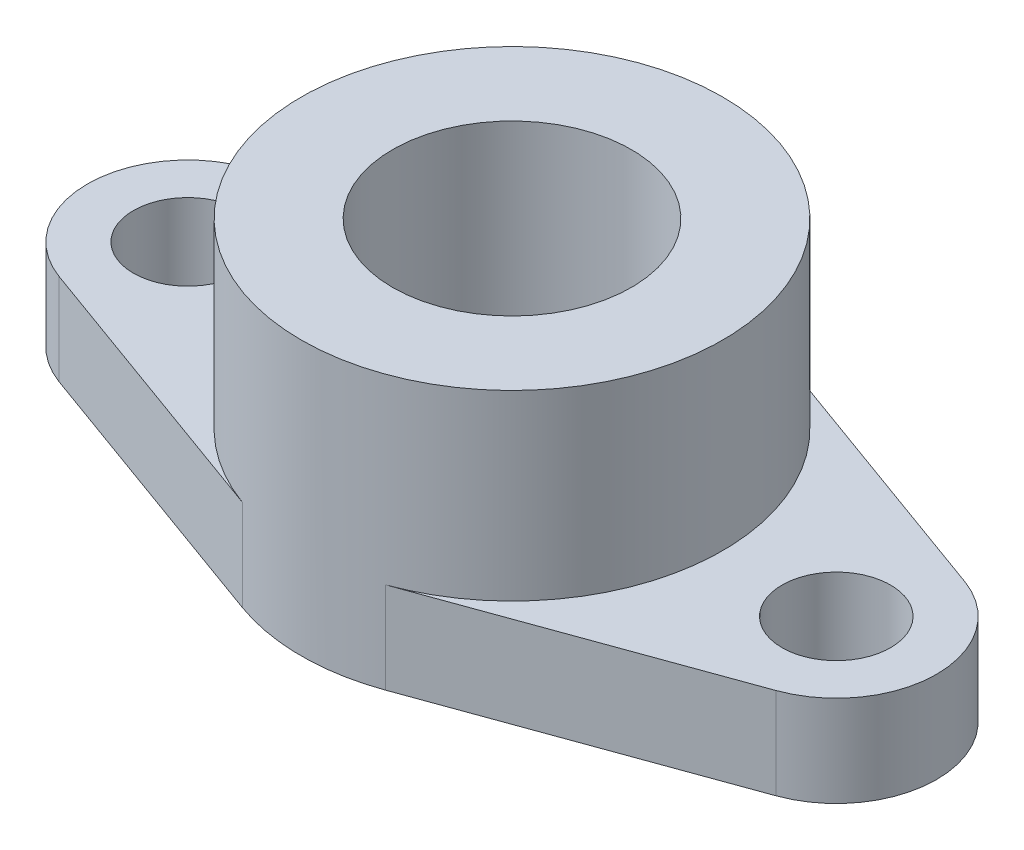
SolidWorks part; units mm, degrees
ref_plane "Front Plane" through (0, 0, 0) normal (0, 0, 1) x (1, 0, 0)
ref_plane "Top Plane" through (0, 0, 0) normal (0, 1, 0) x (1, 0, 0)
ref_plane "Right Plane" through (0, 0, 0) normal (1, 0, 0) x (0, 0, -1)
sketch "Sketch1" plane through (0, 0, 0) normal (0, 1, 0) x (1, 0, 0)
  line L0 (0, 0) -> (6.5484, 0) construction
  line L1 (0, 0) -> (17.78, 0) construction
  line L2 (19.651, 5.172) -> (3.9286, 10.8597)
  line L3 (3.9286, -10.8597) -> (19.651, -5.172)
  line L4 (0, 0) -> (-17.78, 0) construction
  line L5 (-19.651, 5.172) -> (-3.9286, 10.8597)
  line L6 (-19.651, -5.172) -> (-3.9286, -10.8597)
  circle A0 centre (0, 0) radius 4.826
  circle A1 centre (0, 0) radius 6.5484 construction
  arc A2 (3.9286, 10.8597) -> (3.9286, -10.8597) centre (0, 0) ccw construction
  circle A3 centre (17.78, 0) radius 2.9766
  arc A4 (19.651, -5.172) -> (19.651, 5.172) centre (17.78, 0) ccw
  circle A5 centre (0, 0) radius 11.5484 construction
  circle A6 centre (-17.78, 0) radius 2.9766
  arc A7 (-19.651, 5.172) -> (-19.651, -5.172) centre (-17.78, 0) ccw
  arc A10 (-3.9286, -10.8597) -> (3.9286, -10.8597) centre (0, 0) ccw
  arc A11 (3.9286, 10.8597) -> (-3.9286, 10.8597) centre (0, 0) ccw
  dimension "D1" = 9.652
  dimension "D2" = 13.0969
  dimension "D3" = 23.0969
  dimension "D5" = 5.9531
  dimension "D7" = 5.9531
  dimension "D6" = 5.5
  dimension "D4" = 17.78
  dimension "D8" = 17.78
extrude "Boss-Extrude1" add sketch "Sketch1" along normal blind 5
sketch "Sketch2" plane through (0, 5, 0) normal (0, 1, 0) x (1, 0, 0)
  circle A0 centre (0, 0) radius 11.5484
  arc A1 (-3.9286, -10.8597) -> (3.9286, -10.8597) centre (0, 0) ccw construction
  circle A2 centre (0, 0) radius 6.5484
  dimension "D1" = 13.0969
extrude "Boss-Extrude2" add sketch "Sketch2" along normal blind 10
equation "\"z\" = 8\t\t\t\t'number of blades"
equation "\"de\" = 0.43in\t\t\t'entrance eye diameter"
equation "\"de_length\" = 4mm\t\t'entrance eye consistent length"
equation "\"d_exit\" = 0.18in \t\t'throat aka d1"
equation "\"d2\" = 2.1in \t\t\t'outer diameter of the impeller"
equation "\"b2\" = .2in\t\t\t'tip height from disc surface at d2; slightly higher than d_exit"
equation "\"b1\" = \"b2\" + (\"d2\"/2 - \"de\"/2)*tan(\"theta\") \t\t\t'tip height from disc surface at inlet eye"
equation "\"theta\" = 12\t\t\t'angle of blades from inner to outer "
equation "\"ae\" = 3.14*(\"de\"^2)/4\t\t'entrance eye area'"
equation "\"ce\" = 3.14*\"de\"\t\t'entrance eye circumference"
equation "\"av_ratio\" = .325\t\t'ratio of av/ae at N_s of 470, range is .275 to .375, .325 ideal. High ratio means bigger area means smaller blades"
equation "\"av\" = \"ae\"*\"av_ratio\"\t\t'area between just two blades"
equation "\"s_open\" = \"av\"/\"b1\"\t\t'width of open area"
equation "\"s\"=\"ce\" - \"z\"*\"s_open\""
equation "\"min blade thickness\" = .15in"
equation "\"bearing OD\" = 30mm"
equation "\"bearing ID\"= 10mm"
equation "\"bearing depth\"= 9mm"
equation "\"bearing outer race thickness\"= 1mm"
equation "\"bearing inner race thickness\"= 1mm"
equation "\"bearing bore\" = \"bearing depth\" + 1mm"
equation "\"lower seal OD\" = .917in\t\t'this is https://www.mcmaster.com/#9281k121/=174001b"
equation "\"lower seal ID\"= .375in"
equation "\"lower seal depth\" = .625in + .218in"
equation "\"lower seal bore\" = \"lower seal depth\" + 1mm"
equation "\"upper seal OD\" = 1.125in\t'this is https://www.mcmaster.com/#5154t33/=173zuau, needs to be visually inspected before machining!"
equation "\"upper seal ID\"= 0.625in"
equation "\"upper seal depth\"= .25in\t'aka height; these values need to be confirmed by inspection!! We may want to compress the height."
equation "\"upper seal bore\" = \"upper seal depth\" + 1mm"
equation "\"big o-ring thickness\" = .139in"
equation "\"big o-ring OD\" = 2.734in"
equation "\"big o-ring ID\" = 3.012in"
equation "\"big o-ring groove depth\" = \"big o-ring thickness\"*4/5"
equation "\"impeller center height\" = \"impeller base thickness\" + \"b1\"\t'impeller height at de"
equation "\"impeller outer height\" = \"impeller base thickness\" + \"b2\"\t'impeller height at de"
equation "\"impeller upper clearance\"= .5mm"
equation "\"impeller horizontal clearance\"= (\"d2\"*1.15 - \"d2\")/2 \t\t'clearance based on D2-D3 ratio for circular volute, ranges 1.15 to 1.2"
equation "\"impeller bottom clearance\"= .5mm"
equation "\"impeller base thickness\"= 2mm"
equation "\"impeller dowel diameter\" = 2mm"
equation "\"impeller bolt head diameter\" = \"m4 head bore diameter\""
equation "\"impeller bolt head depth\" = 4mm"
equation "\"impeller bolt stop depth\" = 3mm"
equation "\"impeller bolt bore\" = \"m4 clearance\""
equation "\"impeller shaft bore depth\" = 12mm"
equation "\"impeller shaft bore\" = 8mm"
equation "\"impeller boss depth\" = \"impeller shaft bore depth\"+\"impeller bolt stop depth\"+\"impeller bolt head depth\"-\"impeller base thickness\""
equation "\"impeller boss diameter\" = \"upper seal ID\""
equation "\"impeller dowel length\" = 2mm*2 + \"impeller shaft bore\""
equation "\"coupler motor shaft hole ID\"= 8mm"
equation "\"coupler OD\"= 17mm"
equation "\"coupler length\"= 25mm"
equation "\"motor OD\" = 64mm"
equation "\"motor shaft diameter\"= 8mm"
equation "\"motor shaft pride\"= 32mm"
equation "\"motor to bearing plate distance\" = \"motor shaft pride\" + 2mm +\"coupler length\"/2"
equation "\"square plate bolt bore\" = \"m8 clearance\""
equation "\"square plate bolt head diameter\" = 13.5mm"
equation "\"square plate bolt head depth\" = 8mm"
equation "\"square plate bolt pattern diameter\"= 3.5in"
equation "\"motor mount center bore\"= \"coupler OD\"+ 4mm"
equation "\"motor mount post radius\"= ( 3 * \"square plate bolt bore\" ) / 2"
equation "\"motor mount m4 screw hole diameter\"= 4mm"
equation "\"motor mount m4 head diameter\"= 7.25mm"
equation "\"motor mount m4 head depth\"= 4mm"
equation "\"motor mount m4 pattern diamater\" = 30mm"
equation "\"motor mount plate thickness\"= 8mm + \"motor mount m4 head depth\""
equation "\"bearing plate stop ID\" = \"bearing OD\" - 4mm"
equation "\"bearing plate stop depth\" = 3mm"
equation "\"bearing plate thickness\" = \"bearing bore\" + \"bearing plate stop depth\" + \"shaft bearing stop length\""
equation "\"lower seal plate lip depth\" = 2mm"
equation "\"lower seal plate lip ID\" = \"lower seal OD\" - 3mm"
equation "\"lower seal plate thickness\" = \"lower seal plate lip depth\" + \"lower seal bore\""
equation "\"shaft coupler section diameter\" = 8mm"
equation "\"shaft coupler section length\" = \"motor to bearing plate distance\" - \"motor shaft pride\" - 2mm"
equation "\"shaft bearing section diameter\" = \"bearing ID\""
equation "\"shaft bearing section length\" = \"bearing plate stop depth\" + \"bearing depth\""
equation "\"shaft bearing stop diameter\" = \"bearing ID\" + 4mm"
equation "\"shaft bearing stop length\" = 3mm"
equation "\"shaft lower seal section diameter\" = \"lower seal ID\""
equation "\"shaft lower seal section length\" = \"lower seal plate thickness\" + 1mm"
equation "\"shaft impeller section diameter\" = \"impeller shaft bore\""
equation "\"shaft impeller section length\" = \"upper seal plate thickness\" + \"upper seal plate riser\" + \"impeller bottom clearance\" + \"impeller base thickness\" - \"impeller bolt head depth\" - \"impeller bolt stop depth\""
equation "\"upper seal plate thickness\" = \"upper seal plate pressure hole diameter\"+10mm"
equation "\"upper seal plate lip ID\" = \"upper seal OD\" - 3mm"
equation "\"upper seal plate riser\" = 6.59mm \t\t'this number needs to be read from the housing file"
equation "\"upper seal plate pressure hole diameter\" = .125in\t'this is 1/8 drill "
equation "\"upper seal plate pressure tap diameter\" = .328125in \t'this is 21/64 drill for a 1/8 ANPT tap"
equation "\"upper seal plate pressure tap grip\" = 5mm\t\t'this is the area around the tap so it doesn't crack"
equation "\"upper seal plate pressure tap depth\" = 12mm"
equation "\"impeller cavity center height\"= \"impeller bottom clearance\" + \"impeller upper clearance\" + \"impeller center height\""
equation "\"impeller cavity diameter\"= 2 * \"impeller horizontal clearance\" + \"d2\" \t\t\t\t\t\t\t\t\t'called D3 analytically"
equation "\"impeller cavity outer height\"= \"impeller bottom clearance\" + \"impeller upper clearance\" + \"impeller base thickness\" + \"b2\" \t\t'this is height at impeller diameter d2, not at d3"
equation "\"impeller housing thickness\"= \"impeller housing exit threaded diameter\" + 2*\"impeller housing outlet grip\""
equation "\"impeller housing diameter\" = 4.5in"
equation "\"impeller housing bolt count\" = 8"
equation "\"impeller housing bolt diameter\" = \"m6 clearance\""
equation "\"impeller housing bolt pattern diameter\" = 3.5in"
equation "\"impeller housing threaded inlet diameter\" = 0.71875in \t'this is the 23/32 drill size for 1/2 NPT fitting https://www.mcmaster.com/#50715k269/=176pljy"
equation "\"impeller housing threaded inlet depth\"= .6in"
equation "\"impeller housing exit threaded diameter\"= 0.515625in \t\t'this is the 33/64 drill size for 9/16-18 fitting, expecting swagelok SS-8FK0-1-6STH fitting"
equation "\"impeller housing exit threaded depth\"= 10mm"
equation "\"impeller housing diffuser conical angle\"=10"
equation "\"impeller housing diffuser tangent angle\"=5"
equation "\"impeller housing diffuser final diameter\" = .38in\t\t'aka d2'"
equation "\"impeller housing outlet grip\" = 5mm"
equation "\"end mill size\" = 0.375in\t'for 3/8 endmill"
equation "\"m4 clearance\" = 0.171875in \t'this is 11/64 bit for 4.36mm"
equation "\"m4 tap\" = 0.125in\t\t'this is 1/8 bit for 3.17mm"
equation "\"m4 head bore diameter\" = 7.5mm"
equation "\"m4 head bore depth\" = 5mm\t'actual is ~4mm"
equation "\"m6 clearance\" = 0.234375in\t'this is 15/64 bit = 5.95mm, could use 6mm bit, B bit for 6.04mm or 1/4 bit for 6.35mm"
equation "\"m6 tap\" = 5mm\t\t\t'5mm is appropriate, could use 13/64 or #5,6,7"
equation "\"m6 head bore diameter\" = 11mm\t\t"
equation "\"m6 head bore depth\" = 7mm\t'actual is 6mm"
equation "\"m8 clearance\" = 0.3125in\t'this is 5/16in for 7.93mm, could use 8mm, O,P, or 21/64"
equation "\"m8 tap\" = 0.265625in\t\t'this is 17/64 for 6.746875mm"
equation "\"m8 head bore diameter\" = 14mm"
equation "\"m8 head bore depth\" = 9mm\t'actual is 8mm"
equation "\"D1@Sketch1\"=\"impeller housing diffuser final diameter\""
equation "\"D2@Sketch1\"=\"impeller housing exit threaded diameter\""
equation "\"D3@Sketch1\"=\"impeller housing exit threaded diameter\"+\"impeller housing outlet grip\"*2 "
equation "\"D5@Sketch1\"=\"m6 clearance\""
equation "\"D7@Sketch1\"=\"m6 clearance\""
equation "\"D6@Sketch1\"=\"m6 head bore diameter\"/2"
equation "\"D1@Sketch2\"=\"impeller housing exit threaded diameter\""
equation "\"D1@Boss-Extrude2\"=10mm"
equation "\"diffuser cartridge OD\" =.75in"
equation "\"diffuser flange bolt pattern diameter\" = 1.4in"
equation "\"D4@Sketch1\"=\"diffuser flange bolt pattern diameter\"/2"
equation "\"D8@Sketch1\"=\"diffuser flange bolt pattern diameter\"/2"
